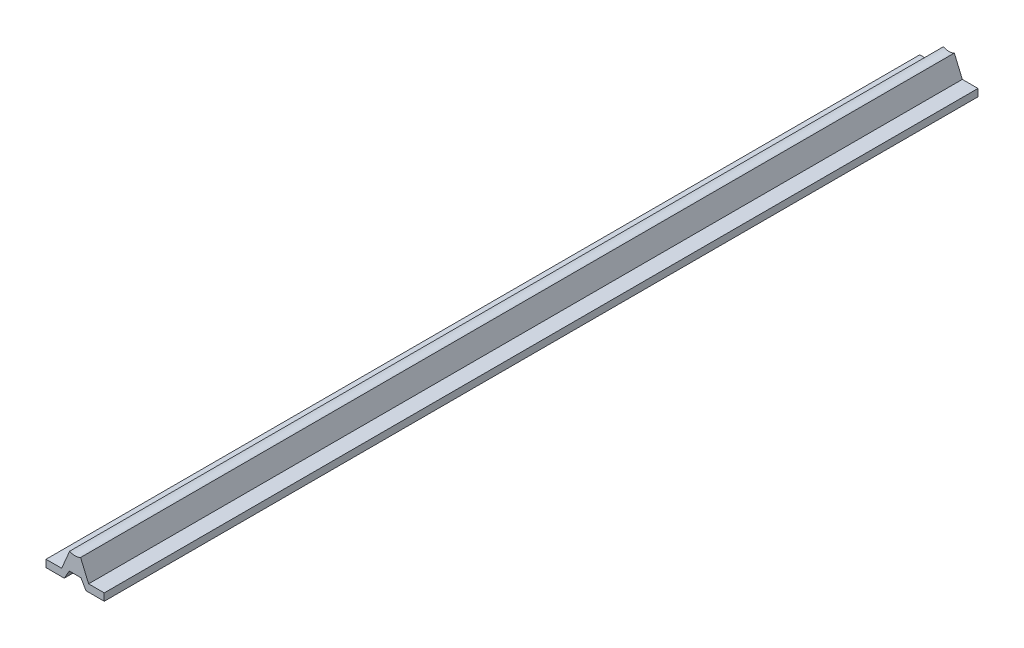
SolidWorks part; units mm, degrees
material "6063-T5"
ref_plane "Front Plane" through (0, 0, 0) normal (0, 0, 1) x (1, 0, 0)
ref_plane "Top Plane" through (0, 0, 0) normal (0, 1, 0) x (1, 0, 0)
ref_plane "Right Plane" through (0, 0, 0) normal (1, 0, 0) x (0, 0, -1)
sketch "Sketch1" plane through (0, 0, 0) normal (0, 0, 1) x (1, 0, 0)
  line L0 (-20, -25) -> (-7.4641, -25)
  line L1 (-7.4641, -25) -> (-4, -19)
  line L2 (-4, -19) -> (4, -19)
  line L3 (4, -19) -> (7.4641, -25)
  line L4 (7.4641, -25) -> (20, -25)
  line L5 (20, -25) -> (20, -20)
  line L6 (20, -20) -> (9.25, -20)
  line L10 (-20, -25) -> (-20, -20)
  line L11 (-20, -20) -> (-9.25, -20)
  line L15 (-9.25, -20) -> (-3.75, -7.0666)
  line L16 (0, -8) -> (0, 0) construction
  line L17 (3.75, -7.0666) -> (9.25, -20)
  line L18 (0, -8) -> (0, -19) construction
  arc A0 (-3.75, -7.0666) -> (3.75, -7.0666) centre (0, 0) ccw
  dimension "D1" = 8
  dimension "D2" = 7.5
  dimension "D3" = 5
  dimension "D4" = 25
  dimension "D5" = 18.5
  dimension "D7" = 20
  dimension "D10" = 8
  dimension "D11" = 60
  dimension "D12" = 6
  dimension "D13" = 40
extrude "Boss-Extrude1" add sketch "Sketch1" along normal blind 600
ref_plane "Плоскость1" through (0, 0, 0) normal (1, 0, 0) x (0, 0, -1)
equation "\"SBR16.Length.X\"= 600мм"
equation "\"SBR16.Length.Y\"= 500мм"
equation "\"SBR16.Length.Z\"= 250мм"
equation "\"D1@Boss-Extrude1\"= \"SBR16.Length.X\""
